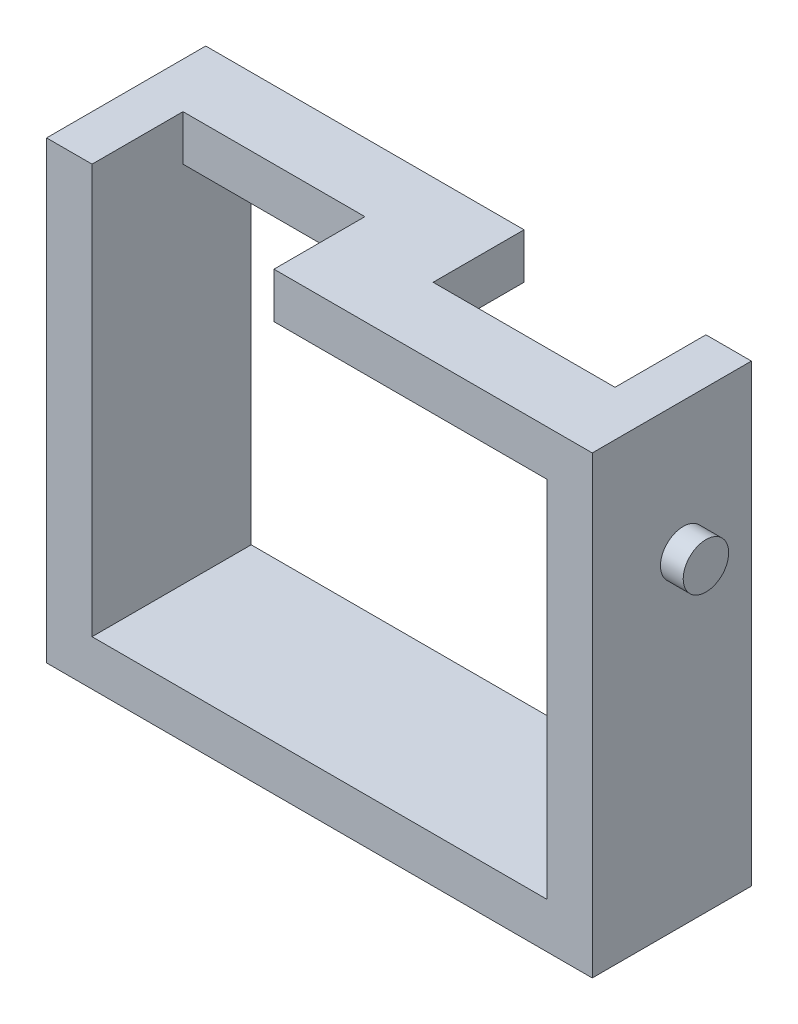
SolidWorks part; units mm, degrees
ref_plane "Front Plane" through (0, 0, 0) normal (0, 0, 1) x (1, 0, 0)
ref_plane "Top Plane" through (0, 0, 0) normal (0, 1, 0) x (1, 0, 0)
ref_plane "Right Plane" through (0, 0, 0) normal (1, 0, 0) x (0, 0, -1)
sketch "Sketch1" plane through (0, 0, 0) normal (0, 0, 1) x (1, 0, 0)
  line L1 (-26.9853, 14.1544) -> (33.0147, 14.1544)
  line L2 (-26.9853, 14.1544) -> (-26.9853, -35.8456)
  line L3 (-26.9853, -35.8456) -> (33.0147, -35.8456)
  line L4 (33.0147, 14.1544) -> (33.0147, -35.8456)
  dimension "D1" = 60
  dimension "D2" = 50
extrude "Boss-Extrude1" add sketch "Sketch1" along normal blind 30
sketch "Sketch2" plane through (0, 0, 30) normal (0, 0, 1) x (1, 0, 0)
  line L0 (-26.9853, 14.1544) -> (-26.9853, -35.8456) construction
  line L1 (-21.9853, 9.1544) -> (28.0147, 9.1544)
  line L2 (-21.9853, 9.1544) -> (-21.9853, -30.8456)
  line L3 (-21.9853, -30.8456) -> (28.0147, -30.8456)
  line L4 (28.0147, 9.1544) -> (28.0147, -30.8456)
  line L5 (33.0147, 14.1544) -> (-26.9853, 14.1544) construction
  dimension "D1" = 40
  dimension "D2" = 50
  dimension "D3" = 5
  dimension "D4" = 5
extrude "Cut-Extrude1" cut sketch "Sketch2" against normal through all
sketch "Sketch3" plane through (0, 14.1544, 0) normal (0, 1, 0) x (1, 0, 0)
  line L0 (33.0147, 0) -> (-26.9853, 0) construction
  line L1 (8.0147, 0) -> (28.0147, 0)
  line L2 (8.0147, 0) -> (8.0147, -22.5)
  line L3 (8.0147, -22.5) -> (28.0147, -22.5)
  line L4 (28.0147, 0) -> (28.0147, -22.5)
  line L5 (33.0147, -30) -> (33.0147, 0) construction
  dimension "D1" = 20
  dimension "D2" = 5
  dimension "D3" = 22.5
extrude "Cut-Extrude2" cut sketch "Sketch3" against normal blind 5
sketch "Sketch4" plane through (0, 14.1544, 0) normal (0, 1, 0) x (1, 0, 0)
  line L0 (33.0147, -30) -> (-26.9853, -30) construction
  line L1 (-21.9853, -30) -> (-1.9853, -30)
  line L2 (-21.9853, -30) -> (-21.9853, -20)
  line L3 (-21.9853, -20) -> (-1.9853, -20)
  line L4 (-1.9853, -30) -> (-1.9853, -20)
  line L5 (-26.9853, -30) -> (-26.9853, 0) construction
  dimension "D1" = 20
  dimension "D2" = 5
  dimension "D3" = 10
extrude "Cut-Extrude3" cut sketch "Sketch4" against normal blind 10
sketch "Sketch5" plane through (0, 14.1544, 0) normal (0, 1, 0) x (1, 0, 0)
  line L0 (8.0147, 0) -> (-26.9853, 0) construction
  line L1 (-28.3531, 0) -> (34.1064, 0)
  line L2 (-28.3531, 0) -> (-28.3531, -12.5)
  line L3 (-28.3531, -12.5) -> (34.1064, -12.5)
  line L4 (34.1064, 0) -> (34.1064, -12.5)
  dimension "D1" = 12.5
extrude "Cut-Extrude4" cut sketch "Sketch5" against normal through all
sketch "Sketch6" plane through (33.0147, 0, 0) normal (1, 0, 0) x (0, 0, -1)
  line L1 (-30, -35.8456) -> (-30, 14.1544) construction
  line L2 (-30, 14.1544) -> (-12.5, 14.1544) construction
  circle A0 centre (-20, -0.3456) radius 2.5
  dimension "D1" = 10
  dimension "D2" = 14.5
extrude "Boss-Extrude2" add sketch "Sketch6" along normal blind 2.5
sketch "Sketch7" plane through (-26.9853, 0, 0) normal (-1, 0, 0) x (0, 0, 1)
  line L0 (30, 14.1544) -> (12.5, 14.1544) construction
  line L1 (30, 14.1544) -> (30, -35.8456) construction
  circle A0 centre (20, -0.3456) radius 2.5
  dimension "D1" = 14.5
  dimension "D2" = 10
extrude "Boss-Extrude3" add sketch "Sketch7" along normal blind 2.5
